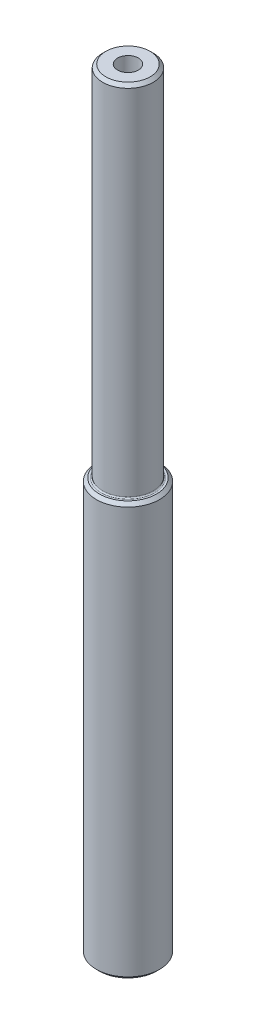
SolidWorks part; units mm, degrees
ref_plane "Front" through (0, 0, 0) normal (0, 0, 1) x (1, 0, 0)
ref_plane "Top" through (0, 0, 0) normal (0, 1, 0) x (1, 0, 0)
ref_plane "Right" through (0, 0, 0) normal (1, 0, 0) x (0, 0, -1)
sketch "Sketch1" plane through (0, 0, 0) normal (0, 0, 1) x (1, 0, 0)
  line L0 (0, 7.4762) -> (0, -8.3651) construction
  line L1 (0, 0) -> (5, 0)
  line L2 (5, 0) -> (5, 65.35)
  line L3 (5, 65.35) -> (4, 65.35)
  line L4 (4, 65.35) -> (4, 122)
  line L5 (4, 122) -> (0, 122)
  line L6 (0, 122) -> (0, 0)
  dimension "D1" = 65.35
  dimension "D2" = 122
  dimension "D3" = 4
  dimension "D4" = 1
revolve "Revolve1" add sketch "Sketch1" angle 360 about L0
hole_wizard "M4 Tapped Hole1" positions "Sketch2" profile "Sketch4" tap size "M4" standard "ISO"
sketch "Sketch2" plane through (0, 0, 0) normal (0, -1, 0) x (-1, 0, 0)
  point P0 (0, 0)
sketch "Sketch4" plane through (0, 0, 0) normal (1, 0, 0) x (0, 0, -1)
  line L0 (0, 0) -> (0, 12.9914)
  line L1 (0, 12.9914) -> (1.65, 12)
  line L2 (1.65, 12) -> (1.65, 0)
  line L5 (1.65, 0) -> (0, 0)
  line L10 (0, 12.9914) -> (-1.65, 12) construction
  line L11 (0, -6.35) -> (0, 107.95) construction
  dimension "Tap Drill Dia." = 3.3
  dimension "Tap Drill Depth" = 12
  dimension "Drill Angle" = 118
cosmetic thread "Hole Thread1" parameters "D1"=8, "D2"=4
ref_plane "Plane1" through (0, 61, 0) normal (0, -1, 0) x (-1, 0, 0)
mirror "Mirror1" about plane through (0, 61, 0) normal (0, -1, 0) of "M4 Tapped Hole1"
cosmetic thread "Hole Thread2" parameters "D1"=8, "D2"=4
fillet "Fillet1" radius 0.2 1 edges at (0, 65.35, 4)
chamfer "Chamfer1" distance 0.5 angle 45 3 edges at (0, 0, 5) (0, 65.35, 5) (0, 122, 4)
